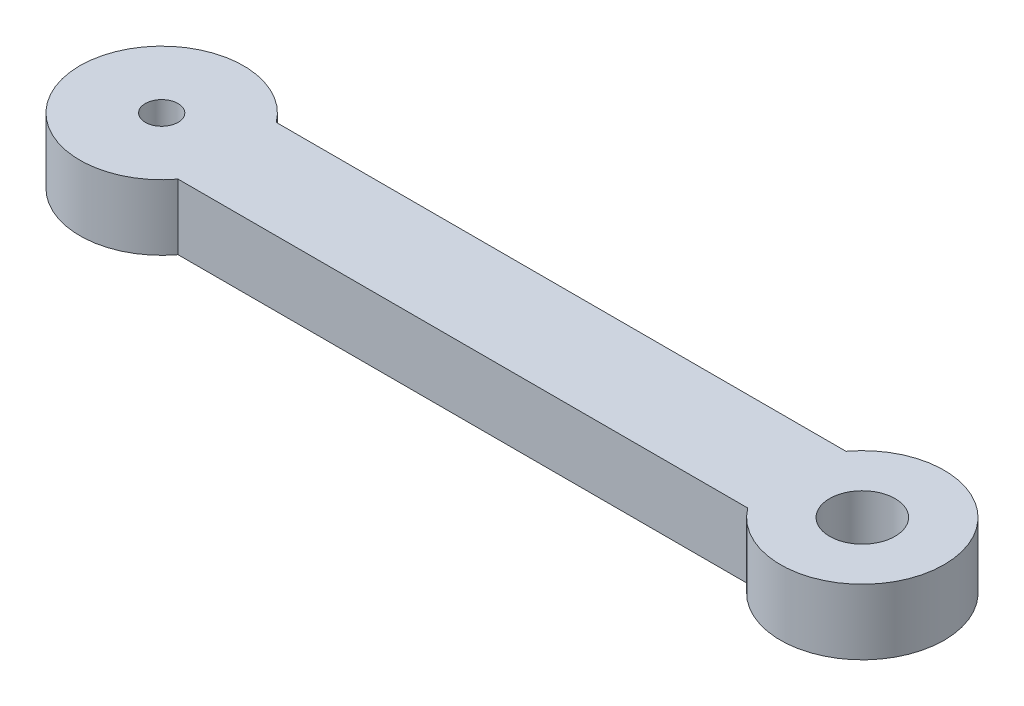
SolidWorks part; units mm, degrees
ref_plane "Front Plane" through (0, 0, 0) normal (0, 0, 1) x (1, 0, 0)
ref_plane "Top Plane" through (0, 0, 0) normal (0, 1, 0) x (1, 0, 0)
ref_plane "Right Plane" through (0, 0, 0) normal (1, 0, 0) x (0, 0, -1)
sketch "Sketch1" plane through (0, 0, 0) normal (0, 1, 0) x (1, 0, 0)
  line L0 (-8.7, 1.5) -> (8.7, 1.5)
  line L1 (-8.7, -1.5) -> (8.7, -1.5)
  line L2 (-10.7, 0) -> (10.7, 0) construction
  arc A0 (8.7, -1.5) -> (8.7, 1.5) centre (10.7, 0) ccw
  arc A1 (-8.7, 1.5) -> (-8.7, -1.5) centre (-10.7, 0) ccw
  circle A2 centre (10.7, 0) radius 1
  circle A3 centre (-10.7, 0) radius 0.5
  dimension "D1" = 5
  dimension "D3" = 1
  dimension "D5" = 2
  dimension "D2" = 21.4
  dimension "D4" = 3
extrude "Boss-Extrude1" add sketch "Sketch1" along normal blind 2
